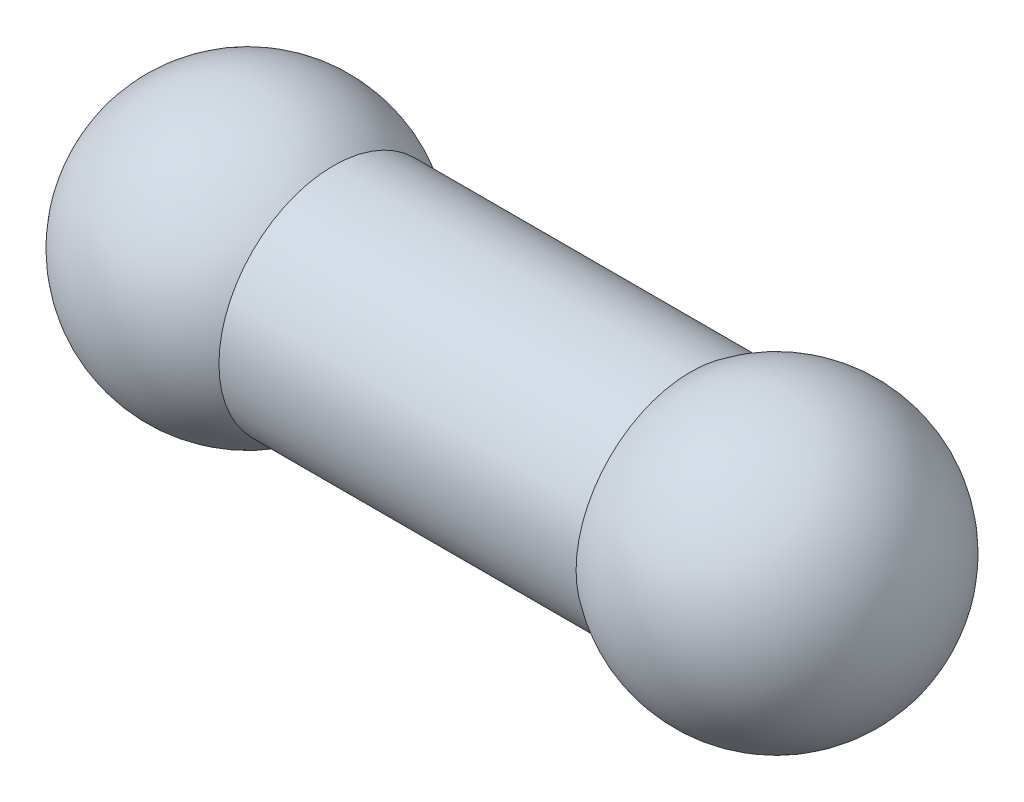
SolidWorks part; units mm, degrees
ref_plane "Ön Düzlem" through (0, 0, 0) normal (0, 0, 1) x (1, 0, 0)
ref_plane "Üst Düzlem" through (0, 0, 0) normal (0, 1, 0) x (1, 0, 0)
ref_plane "Sağ Düzlem" through (0, 0, 0) normal (1, 0, 0) x (0, 0, -1)
sketch "Çizim3" plane through (0, 0, 0) normal (0, 0, 1) x (1, 0, 0)
  line L0 (-18.8246, 4.8083) -> (-3.8246, 4.8083)
  line L1 (-0.2357, 0) -> (-22.4134, 0) construction
  line L3 (-40.9506, 0) -> (16.6709, 0) construction
  line L4 (-28.4134, 0) -> (5.7643, 0)
  arc A0 (-18.8246, 4.8083) -> (-28.4134, 0) centre (-22.4134, 0) ccw
  arc A1 (5.7643, 0) -> (-3.8246, 4.8083) centre (-0.2357, 0) ccw
  dimension "D1" = 12
  dimension "D2" = 12
  dimension "D3" = 15
revolve "Döndür2" add sketch "Çizim3" angle 360 about L4
